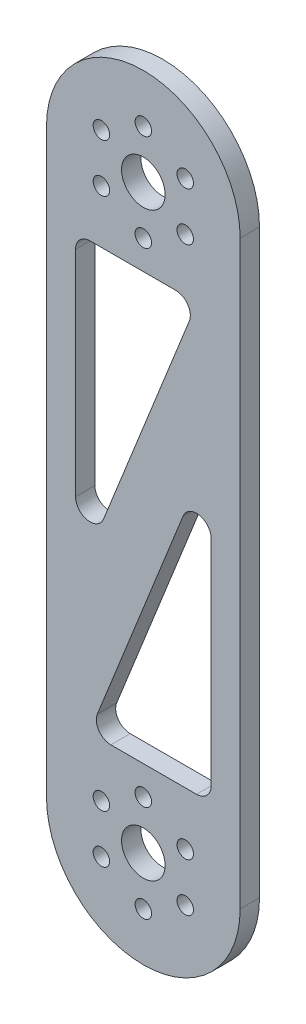
SolidWorks part; units mm, degrees
ref_plane "前视基准面" through (0, 0, 0) normal (0, 0, 1) x (1, 0, 0)
ref_plane "上视基准面" through (0, 0, 0) normal (0, 1, 0) x (1, 0, 0)
ref_plane "右视基准面" through (0, 0, 0) normal (1, 0, 0) x (0, 0, -1)
sketch "草图1" plane through (0, 0, 0) normal (0, 0, 1) x (1, 0, 0)
  line L0 (0, -43.0625) -> (0, 43.0625) construction
  line L1 (20, -60) -> (20, 60)
  line L3 (-20, 60) -> (-20, -60)
  arc A0 (20, 60) -> (-20, 60) centre (0, 60) ccw
  arc A1 (-20, -60) -> (20, -60) centre (0, -60) ccw
  circle A2 centre (0, 60) radius 4.5
  circle A3 centre (0, -60) radius 4.5
  point P4 (0, 0)
  dimension "D1" = 40
  dimension "D2" = 40
  dimension "D5" = 9
  dimension "D6" = 9
  dimension "D3" = 120
  dimension "D4" = 60
extrude "凸台-拉伸2" add sketch "草图1" along normal blind 4
sketch "草图4" plane through (0, 0, 4) normal (0, 0, 1) x (1, 0, 0)
  line L26 (20, -60) -> (20, 60) construction
  line L27 (-20, -50) -> (20, -50) construction
  line L28 (-20, -50) -> (-20, 50) construction
  line L29 (-20, 50) -> (20, 50) construction
  line L30 (20, -50) -> (20, 50) construction
  line L31 (-20, -50) -> (20, 50) construction
  line L32 (-20, 50) -> (20, -50) construction
  line L33 (-14, -18.8445) -> (11.1378, 44)
  line L34 (-14, 44) -> (11.1378, 44)
  line L35 (-14, -18.8445) -> (-14, 44)
  line L36 (14, -44) -> (14, 18.8445)
  line L37 (-11.1378, -44) -> (14, 18.8445)
  line L38 (-11.1378, -44) -> (14, -44)
  point P0 (0, 0)
  dimension "D1" = 100
  dimension "D2" = 6
  dimension "D3" = 6
extrude "切除-拉伸1" cut sketch "草图4" against normal through all
fillet "圆角1" radius 3 6 edges at (14, 18.8445, 2) (14, -44, 2) (-11.1378, -44, 2) (-14, -18.8445, 2) (11.1378, 44, 2) (-14, 44, 2)
sketch "草图6" plane through (0, 0, 4) normal (0, 0, 1) x (1, 0, 0)
  line L0 (0, -60) -> (0, 60) construction
  line L1 (0, 60) -> (8.6603, 55) construction
  line L2 (55, 0) -> (-55, 0) construction
  line L3 (0, 60) -> (8.6603, 65) construction
  line L4 (0, 70) -> (0, 60) construction
  line L5 (-8.6603, 65) -> (0, 60) construction
  line L6 (0, 60) -> (-8.6603, 55) construction
  circle A0 centre (0, 50) radius 1.7
  circle A1 centre (-8.6603, 55) radius 1.7
  circle A2 centre (-8.6603, 65) radius 1.7
  circle A3 centre (0, 70) radius 1.7
  circle A4 centre (8.6603, 65) radius 1.7
  circle A5 centre (8.6603, 55) radius 1.7
  circle A6 centre (0, -70) radius 1.7
  circle A7 centre (-8.6603, -65) radius 1.7
  circle A8 centre (-8.6603, -55) radius 1.7
  circle A9 centre (0, -50) radius 1.7
  circle A10 centre (8.6603, -55) radius 1.7
  circle A11 centre (8.6603, -65) radius 1.7
  point P16 (0, 60)
  dimension "D1" = 3.4
  dimension "D5" = 10
  dimension "D2" = 10
  dimension "D3" = 60
  dimension "D4" = 6
extrude "切除-拉伸2" cut sketch "草图6" against normal through all
